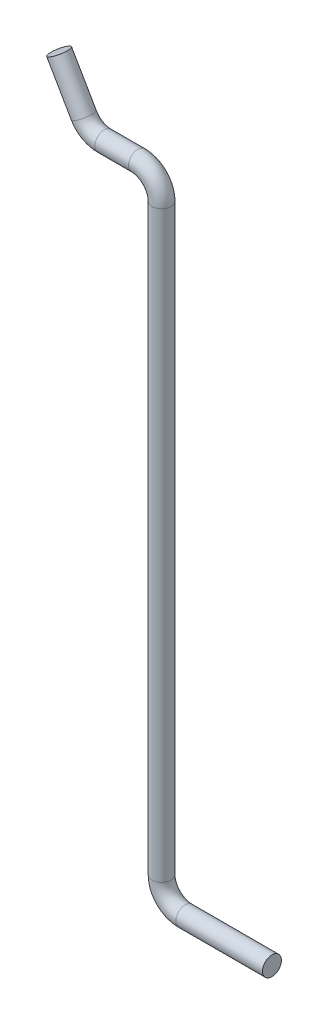
SolidWorks part; units mm, degrees
material "1023 碳钢板 (SS)"
ref_plane "前视基准面" through (0, 0, 0) normal (0, 0, 1) x (1, 0, 0)
ref_plane "上视基准面" through (0, 0, 0) normal (0, 1, 0) x (1, 0, 0)
ref_plane "右视基准面" through (0, 0, 0) normal (1, 0, 0) x (0, 0, -1)
other "Configuration Table"
sketch "草图1" plane through (0, 0, 0) normal (0, 0, 1) x (1, 0, 0)
  line L0 (-2, 3.4641) -> (-0.433, 0.75)
  line L1 (0.866, 0) -> (3, 0)
  line L2 (4.5, -1.5) -> (4.5, -38.5)
  line L3 (6, -40) -> (11.5, -40)
  arc A0 (4.5, -38.5) -> (6, -40) centre (6, -38.5) ccw
  arc A1 (3, 0) -> (4.5, -1.5) centre (3, -1.5) cw
  arc A2 (-0.433, 0.75) -> (0.866, 0) centre (0.866, 1.5) ccw
  point P8 (4.5, -40)
  point P11 (4.5, 0)
  point P14 (0, 0)
  dimension "D6" = 1.5
  dimension "D1" = 30
  dimension "D2" = 4.5
  dimension "D3" = 4
  dimension "D4" = 40
  dimension "D5" = 7
sweep "扫描1" add path "草图1" circular profile diameter 1.2 parameters "D3"=1.2
